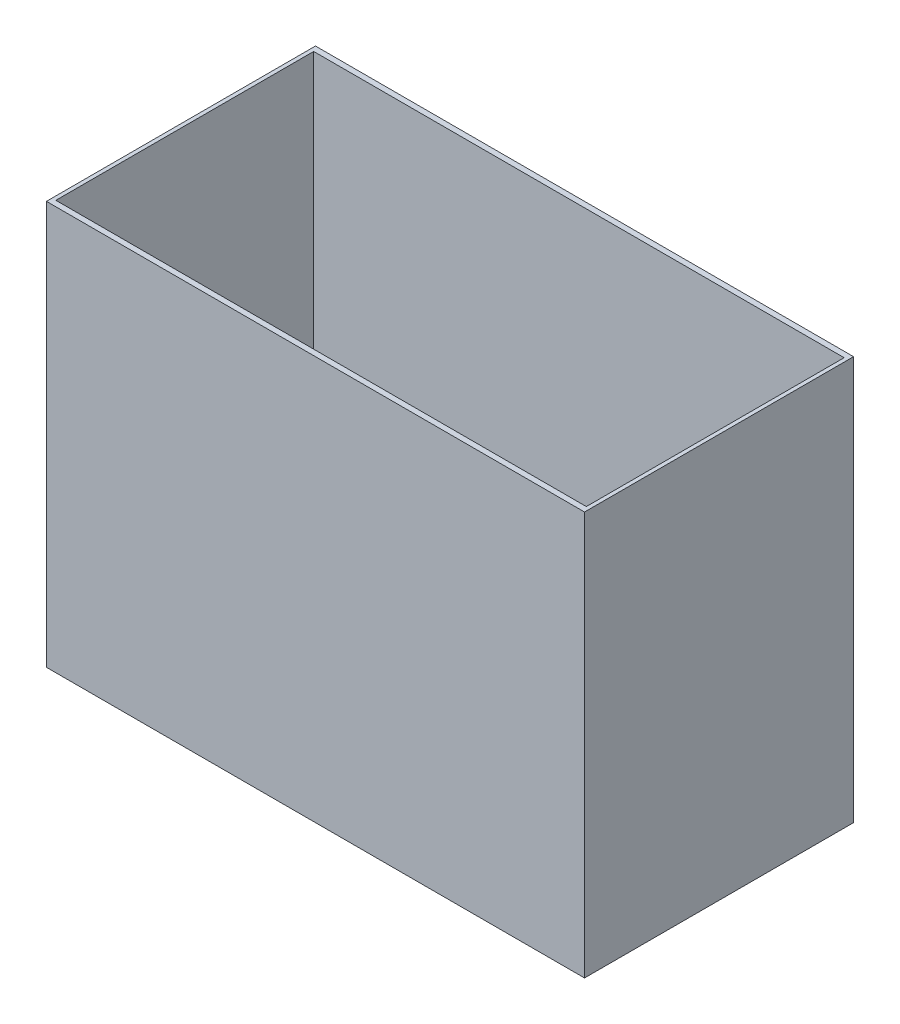
SolidWorks part; units mm, degrees
ref_plane "Front Plane" through (0, 0, 0) normal (0, 0, 1) x (1, 0, 0)
ref_plane "Top Plane" through (0, 0, 0) normal (0, 1, 0) x (1, 0, 0)
ref_plane "Right Plane" through (0, 0, 0) normal (1, 0, 0) x (0, 0, -1)
other "Bounding Box"
ref_plane "Default Plane" through (-292.1, 0, -139.7) normal (0, 1, 0) x (1, 0, 0)
sketch "Sketch1" plane through (0, 0, 0) normal (0, 1, 0) x (1, 0, 0)
  line L0 (-292.1, 0) -> (292.1, 0) construction
  line L1 (-292.1, 139.7) -> (292.1, 139.7)
  line L2 (-292.1, 139.7) -> (-292.1, -139.7)
  line L3 (-292.1, -139.7) -> (292.1, -139.7)
  line L4 (292.1, 139.7) -> (292.1, -139.7)
  line L5 (0, 139.7) -> (0, -139.7) construction
  point P8 (0, 0)
  dimension "D1" = 584.2
  dimension "D2" = 279.4
extrude "Boss-Extrude1" add sketch "Sketch1" along normal blind 12.7
sketch "Sketch2" plane through (0, 12.7, 0) normal (0, 1, 0) x (1, 0, 0)
  line L0 (-245.9259, -63.5) -> (-55.3589, -63.5) construction
  line L1 (-241.3, -120.6497) -> (-152.4, -120.6497)
  line L2 (-241.3, -120.6497) -> (-241.3, -101.5997)
  line L3 (-241.3, -101.5997) -> (-152.4, -101.5997)
  line L4 (-152.4, -120.6497) -> (-152.4, -101.5997)
  line L5 (-241.3, -120.6497) -> (-152.4, -101.5997) construction
  line L6 (-241.3, -101.5997) -> (-152.4, -120.6497) construction
  line L7 (-292.1, 139.7) -> (-292.1, -139.7) construction
  line L8 (-292.1, 0) -> (292.1, 0) construction
  line L9 (292.1, -139.7) -> (292.1, 139.7) construction
  line L10 (0, 0) -> (0, 121.6784) construction
  line L11 (241.3, -101.5997) -> (152.4, -120.6497) construction
  line L12 (241.3, -120.6497) -> (152.4, -101.5997) construction
  line L13 (152.4, -120.6497) -> (152.4, -101.5997)
  line L14 (241.3, -101.5997) -> (152.4, -101.5997)
  line L15 (241.3, -120.6497) -> (241.3, -101.5997)
  line L16 (241.3, -120.6497) -> (152.4, -120.6497)
  point P0 (-196.85, -111.1247)
  point P17 (196.85, -111.1247)
  dimension "D1" = 19.05
  dimension "D2" = 88.9
  dimension "D3" = 38.0997
  dimension "D4" = 50.8
  dimension "D5" = 63.5
extrude "Boss-Extrude2" [suppressed] add sketch "Sketch2" along normal blind 304.8 separate body contours L2 L1 L4 L3
pattern_linear "LPattern1" [suppressed] count 2 spacing 304.8
pattern_linear "LPattern2" [suppressed] count 2 spacing 215.9
sketch "Sketch3" plane through (0, 0, 0) normal (0, 1, 0) x (1, 0, 0)
  line L1 (-304.8, -152.4) -> (304.8, -152.4)
  line L2 (-304.8, -152.4) -> (-304.8, 152.4)
  line L3 (-304.8, 152.4) -> (304.8, 152.4)
  line L4 (304.8, -152.4) -> (304.8, 152.4)
  line L5 (-304.8, -152.4) -> (304.8, 152.4) construction
  line L6 (-304.8, 152.4) -> (304.8, -152.4) construction
  line L7 (-300.482, -146.05) -> (300.482, -146.05)
  line L8 (-300.482, -146.05) -> (-300.482, 146.05)
  line L9 (-300.482, 146.05) -> (300.482, 146.05)
  line L10 (300.482, -146.05) -> (300.482, 146.05)
  line L11 (-300.482, -146.05) -> (300.482, 146.05) construction
  line L12 (-300.482, 146.05) -> (300.482, -146.05) construction
  point P0 (0, 0)
  point P6 (0, 0)
  dimension "D1" = 609.6
  dimension "D2" = 304.8
  dimension "D3" = 292.1
  dimension "D4" = 600.964
extrude "Boss-Extrude3" add sketch "Sketch3" along normal blind 457.2 separate body
sketch "Sketch4" plane through (0, 12.7, 0) normal (0, 1, 0) x (1, 0, 0)
  line L0 (292.1, 139.7) -> (-292.1, 139.7) construction
  line L1 (292.1, -139.7) -> (292.1, 139.7) construction
  circle A0 centre (254, 101.6) radius 2.7781
  dimension "D1" = 5.5562
  dimension "D2" = 38.1
  dimension "D3" = 38.1
extrude "Cut-Extrude1" cut sketch "Sketch4" against normal through all
sketch "Sketch6" plane through (0, 0, 0) normal (0, -1, 0) x (1, 0, 0)
  circle A0 centre (254, -101.6) radius 6.35
  circle A1 centre (254, -101.6) radius 2.7781 construction
  point P2 (247.1988, 78.7391)
  dimension "D1" = 12.7
extrude "Cut-Extrude2" cut sketch "Sketch6" against normal blind 2.54
mirror "Mirror1" about plane through (0, 0, 0) normal (0, 0, 1) of "Cut-Extrude2", "Cut-Extrude1"
sketch "Sketch7" plane through (0, 12.7, 0) normal (0, 1, 0) x (1, 0, 0)
  line L0 (292.1, 0) -> (49.4912, 0) construction
  line L1 (292.1, -139.7) -> (292.1, 139.7) construction
  circle A0 centre (190.5, 0) radius 4 construction
  circle A1 centre (190.5, 0) radius 2.7781
  dimension "D1" = 8
  dimension "D2" = 5.5562
  dimension "D3" = 101.6
extrude "Cut-Extrude3" cut sketch "Sketch7" against normal through all
